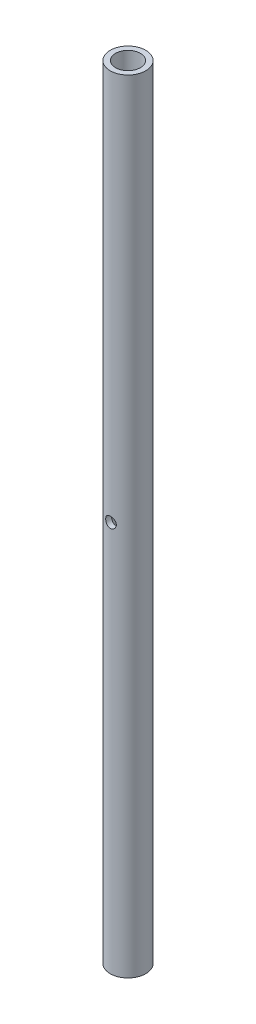
SolidWorks part; units mm, degrees
material "Thornel Mat VMA"
ref_plane "Ön Düzlem" through (0, 0, 0) normal (0, 0, 1) x (1, 0, 0)
ref_plane "Üst Düzlem" through (0, 0, 0) normal (0, 1, 0) x (1, 0, 0)
ref_plane "Sağ Düzlem" through (0, 0, 0) normal (1, 0, 0) x (0, 0, -1)
sketch "Çizim1" plane through (0, 0, 0) normal (0, 1, 0) x (1, 0, 0)
  circle A0 centre (0, 0) radius 5
  circle A1 centre (0, 0) radius 3.5
  dimension "D1" = 10
  dimension "D2" = 7
extrude "Yükseklik-Ekstrüzyon1" add sketch "Çizim1" along normal blind 220
sketch "Çizim2" plane through (0, 0, 0) normal (0, 0, 1) x (1, 0, 0)
  line L0 (-5, 110) -> (5, 110) construction
  line L1 (-5, 220) -> (-5, 0) construction
  line L2 (5, 0) -> (5, 220) construction
  circle A0 centre (0, 110) radius 1.5
  dimension "D1" = 3
extrude "Kes-Ekstrüzyon1" cut sketch "Çizim2" against normal mid plane 30
